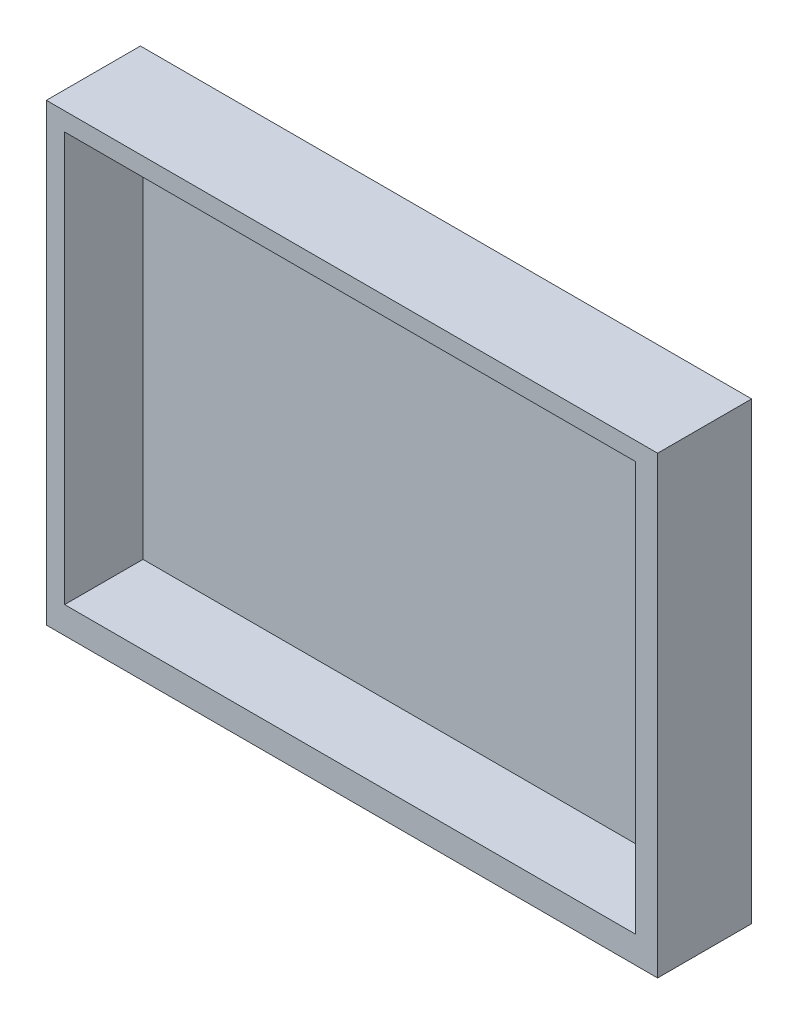
SolidWorks part; units mm, degrees
ref_plane "前视基准面" through (0, 0, 0) normal (0, 0, 1) x (1, 0, 0)
ref_plane "上视基准面" through (0, 0, 0) normal (0, 1, 0) x (1, 0, 0)
ref_plane "右视基准面" through (0, 0, 0) normal (1, 0, 0) x (0, 0, -1)
other "Configuration Table"
sketch "草图1" plane through (0, 0, 0) normal (0, 0, 1) x (1, 0, 0)
  line L1 (0, 0) -> (117, 0)
  line L2 (0, 0) -> (0, -87)
  line L3 (0, -87) -> (117, -87)
  line L4 (117, 0) -> (117, -87)
  line L5 (3.5, -3.5) -> (113.5, -3.5)
  line L6 (3.5, -3.5) -> (3.5, -83.5)
  line L7 (3.5, -83.5) -> (113.5, -83.5)
  line L8 (113.5, -3.5) -> (113.5, -83.5)
  dimension "D1" = 117
  dimension "D2" = 87
  dimension "D3" = 110
  dimension "D4" = 80
  dimension "D5" = 3.5
  dimension "D6" = 3.5
extrude "凸台-拉伸1" add sketch "草图1" along normal blind 3 contours L8 L5 L6 L7 | L4 L1 L2 L3 L5 L8 L7 L6
sketch "草图2" plane through (0, 0, 3) normal (0, 0, 1) x (1, 0, 0)
  line L1 (0, 0) -> (117, 0)
  line L2 (0, 0) -> (0, -87)
  line L3 (0, -87) -> (117, -87)
  line L4 (117, 0) -> (117, -87)
  line L5 (3.5, -3.5) -> (112.7794, -3.5)
  line L6 (3.5, -3.5) -> (3.5, -81.8529)
  line L7 (3.5, -81.8529) -> (112.7794, -81.8529)
  line L8 (112.7794, -3.5) -> (112.7794, -81.8529)
  dimension "D1" = 3.5
  dimension "D2" = 3.5
extrude "凸台-拉伸2" add sketch "草图2" along normal blind 15
